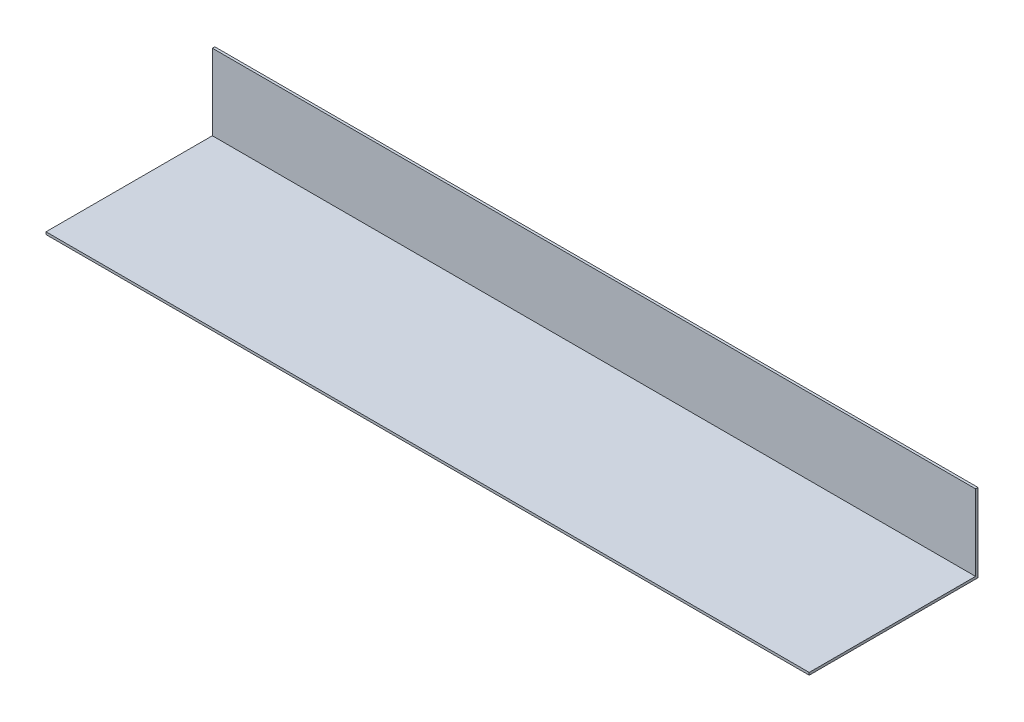
SolidWorks part; units mm, degrees
material "Alloy Steel"
ref_plane "Front Plane" through (0, 0, 0) normal (0, 0, 1) x (1, 0, 0)
ref_plane "Top Plane" through (0, 0, 0) normal (0, 1, 0) x (1, 0, 0)
ref_plane "Right Plane" through (0, 0, 0) normal (1, 0, 0) x (0, 0, -1)
sketch "Sketch1" plane through (0, 0, 0) normal (0, 0, 1) x (1, 0, 0)
  line L1 (-247.65, -25.4) -> (247.65, -25.4)
  line L2 (-247.65, -25.4) -> (-247.65, 25.4)
  line L3 (-247.65, 25.4) -> (247.65, 25.4)
  line L4 (247.65, -25.4) -> (247.65, 25.4)
  line L5 (-247.65, -25.4) -> (247.65, 25.4) construction
  line L6 (-247.65, 25.4) -> (247.65, -25.4) construction
  point P0 (0, 0)
extrude "Boss-Extrude1" add sketch "Sketch1" along normal blind 1.5875
sketch "Sketch2" plane through (0, 0, 1.5875) normal (0, 0, 1) x (1, 0, 0)
  line L0 (247.65, -25.4) -> (247.65, 25.4) construction
  line L1 (-247.65, -25.4) -> (247.65, -25.4)
  line L2 (-247.65, -25.4) -> (-247.65, -23.8125)
  line L3 (-247.65, -23.8125) -> (247.65, -23.8125)
  line L4 (247.65, -25.4) -> (247.65, -23.8125)
extrude "Boss-Extrude2" add sketch "Sketch2" along normal blind 107.95
